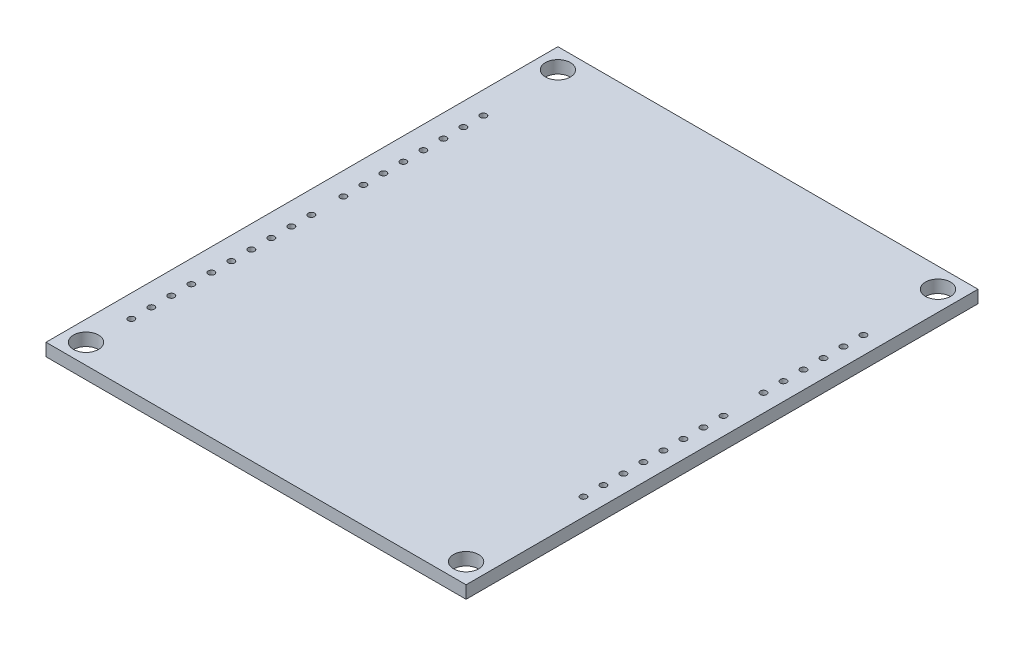
SolidWorks part; units mm, degrees
material "E-Glass Fiber"
ref_plane "Front Plane" through (0, 0, 0) normal (0, 0, 1) x (1, 0, 0)
ref_plane "Top Plane" through (0, 0, 0) normal (0, 1, 0) x (1, 0, 0)
ref_plane "Right Plane" through (0, 0, 0) normal (1, 0, 0) x (0, 0, -1)
sketch "Sketch1" plane through (0, 0, 0) normal (0, 1, 0) x (1, 0, 0)
  line L1 (-0.3056, 10.8084) -> (-53.6456, 10.8084)
  line L2 (-0.3056, 10.8084) -> (-0.3056, 75.8084)
  line L4 (-53.6456, 10.8084) -> (-53.6456, 75.8084)
  line L5 (-53.6456, 75.8084) -> (-0.3056, 75.8084)
  circle A0 centre (-51.1056, 73.2684) radius 1.5875
  circle A1 centre (-2.8456, 73.2684) radius 1.5875
  circle A2 centre (-2.8456, 13.3484) radius 1.5875
  circle A3 centre (-51.1056, 13.3484) radius 1.5875
  dimension "D8" = 2.54
  dimension "D2" = 2.54
  dimension "D3" = 2.54
  dimension "D4" = 2.54
  dimension "D5" = 2.54
  dimension "D6" = 2.54
  dimension "D7" = 2.54
  dimension "D9" = 65
  dimension "D13" = 2.54
  dimension "D15" = 50.8
extrude "Boss-Extrude1" add sketch "Sketch1" against normal blind 1.6
sketch "Sketch2" plane through (0, 0, 0) normal (0, 1, 0) x (1, 0, 0)
  line L0 (0, -0.9075) -> (0, 0.9075) construction
  line L1 (-0.9075, 0) -> (0.9075, 0) construction
  circle A0 centre (-2.54, 27.94) radius 0.4
  dimension "D1" = 0.8
  dimension "D2" = 2.54
  dimension "D3" = 27.94
extrude "Cut-Extrude1" cut sketch "Sketch2" against normal blind 1.65
sketch "Sketch3" plane through (0, 0, 0) normal (0, 1, 0) x (1, 0, 0)
  line L0 (0, -0.9075) -> (0, 0.9075) construction
  line L1 (-0.9075, 0) -> (0.9075, 0) construction
  circle A0 centre (-50.8, 18.796) radius 0.4
  dimension "D2" = 0.8
  dimension "D1" = 50.8
  dimension "D3" = 18.796
extrude "Cut-Extrude2" cut sketch "Sketch3" against normal blind 1.65
pattern_linear "LPattern1" count 15 spacing 2.54 along (0, 0, -1) skipping (8, 0) of "Cut-Extrude1"
sketch "Sketch4" plane through (0, 0, 0) normal (0, 1, 0) x (1, 0, 0)
  line L0 (-0.9075, 0) -> (0.9075, 0) construction
  line L1 (0, -0.9075) -> (0, 0.9075) construction
  circle A0 centre (-50.8, 45.72) radius 0.4
  dimension "D3" = 0.8
  dimension "D1" = 45.72
  dimension "D2" = 50.8
extrude "Cut-Extrude3" cut sketch "Sketch4" against normal blind 1.65
pattern_linear "LPattern2" count 10 spacing 2.54 along (0, 0, -1) of "Cut-Extrude2"
pattern_linear "LPattern3" count 9 spacing 2.54 along (0, 0, -1) skipping (8, 0) of "Cut-Extrude3"
sketch "Sketch5" plane through (0, 0, 0) normal (0, 1, 0) x (1, 0, 0)
  line L0 (-27.89, 66.18) -> (-27.89, 63.64) construction
  line L1 (-30.43, 66.18) -> (-25.35, 66.18) construction
  line L2 (-30.43, 66.18) -> (-30.43, 63.64) construction
  line L3 (-30.43, 63.64) -> (-25.35, 63.64) construction
  line L4 (-25.35, 66.18) -> (-25.35, 63.64) construction
  line L5 (-0.9075, 0) -> (0.9075, 0) construction
  line L6 (0, -0.9075) -> (0, 0.9075) construction
  circle A0 centre (-30.43, 66.18) radius 0.4
  circle A1 centre (-27.89, 66.18) radius 0.4
  circle A2 centre (-25.35, 66.18) radius 0.4
  circle A3 centre (-25.35, 63.64) radius 0.4
  circle A4 centre (-27.89, 63.64) radius 0.4
  circle A5 centre (-30.43, 63.64) radius 0.4
  circle A6 centre (-47.498, 15.748) radius 0.4
  circle A7 centre (-47.498, 18.288) radius 0.4
  circle A8 centre (-47.498, 20.828) radius 0.4
  circle A9 centre (-44.958, 20.828) radius 0.4
  circle A10 centre (-44.958, 18.288) radius 0.4
  circle A11 centre (-44.958, 15.748) radius 0.4
  circle A12 centre (-42.418, 18.288) radius 0.4
  circle A13 centre (-42.418, 20.828) radius 0.4
  circle A14 centre (-39.878, 20.828) radius 0.4
  circle A15 centre (-39.878, 18.288) radius 0.4
  circle A16 centre (-26.035, 20.955) radius 0.5
  circle A17 centre (-26.035, 15.875) radius 0.5
  dimension "D4" = 0.8
  dimension "D14" = 1
  dimension "D1" = 2.54
  dimension "D2" = 2.54
  dimension "D3" = 2.54
  dimension "D5" = 63.64
  dimension "D6" = 30.43
  dimension "D7" = 2.54
  dimension "D8" = 2.54
  dimension "D9" = 2.54
  dimension "D10" = 2.54
  dimension "D11" = 2.54
  dimension "D12" = 47.498
  dimension "D13" = 15.748
  dimension "D15" = 5.08
  dimension "D16" = 15.875
  dimension "D17" = 26.035
sketch "Sketch6" plane through (0, 0, 0) normal (0, 1, 0) x (1, 0, 0)
  line L0 (0, -55) -> (0, 55) construction
  line L1 (-55, 0) -> (55, 0) construction
  line L2 (-20.193, 29.845) -> (-20.193, 32.385) construction
  circle A0 centre (-20.193, 29.845) radius 0.4
  circle A1 centre (-12.573, 29.845) radius 0.4
  circle A2 centre (-20.193, 32.385) radius 0.4
  circle A3 centre (-12.573, 32.385) radius 0.4
  circle A4 centre (-20.193, 34.925) radius 0.4
  circle A5 centre (-12.573, 34.925) radius 0.4
  circle A6 centre (-20.193, 37.465) radius 0.4
  circle A7 centre (-12.573, 37.465) radius 0.4
  circle A8 centre (-20.193, 40.005) radius 0.4
  circle A9 centre (-12.573, 40.005) radius 0.4
  circle A10 centre (-20.193, 42.545) radius 0.4
  circle A11 centre (-12.573, 42.545) radius 0.4
  circle A12 centre (-20.193, 45.085) radius 0.4
  circle A13 centre (-12.573, 45.085) radius 0.4
  circle A14 centre (-20.193, 47.625) radius 0.4
  circle A15 centre (-12.573, 47.625) radius 0.4
  circle A16 centre (-20.193, 50.165) radius 0.4
  circle A17 centre (-12.573, 50.165) radius 0.4
  circle A18 centre (-20.193, 52.705) radius 0.4
  circle A19 centre (-12.573, 52.705) radius 0.4
  circle A20 centre (-20.193, 55.245) radius 0.4
  circle A21 centre (-12.573, 55.245) radius 0.4
  circle A22 centre (-20.193, 57.785) radius 0.4
  circle A23 centre (-12.573, 57.785) radius 0.4
  circle A24 centre (-20.193, 60.325) radius 0.4
  circle A25 centre (-12.573, 60.325) radius 0.4
  circle A26 centre (-20.193, 62.865) radius 0.4
  circle A27 centre (-12.573, 62.865) radius 0.4
  dimension "D1" = 0.8
  dimension "D2" = 7.62
  dimension "D3" = 12.573
  dimension "D4" = 29.845
  dimension "D6" = 2.54
  dimension "D5" = 14
sketch "Sketch7" plane through (0, 0, 0) normal (0, 1, 0) x (1, 0, 0)
  line L0 (-55, 0) -> (55, 0) construction
  line L1 (0, -55) -> (0, 55) construction
  circle A0 centre (-50.8, 96.52) radius 0.4
  circle A1 centre (-50.8, 93.98) radius 0.4
  dimension "D1" = 0.8
  dimension "D2" = 2.54
  dimension "D3" = 96.52
  dimension "D4" = 50.8
equation "\"D13@Sketch5\"=0.001*25.4*620"
equation "\"D16@Sketch5\"=625*0.001*25.4"
equation "\"D17@Sketch5\"=1025*0.001*25.4"
